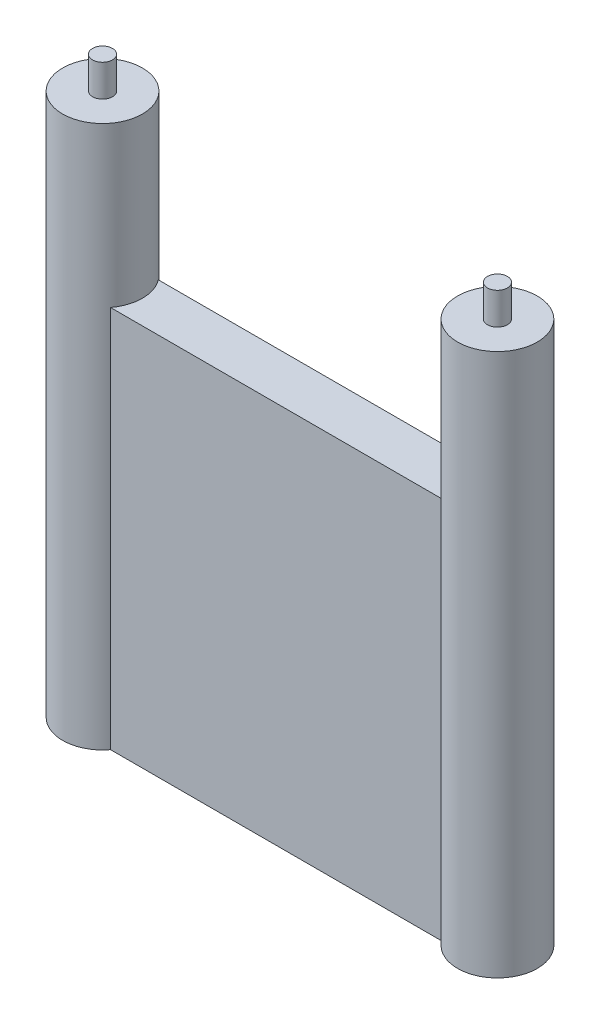
SolidWorks part; units mm, degrees
ref_plane "Front Plane" through (0, 0, 0) normal (0, 0, 1) x (1, 0, 0)
ref_plane "Top Plane" through (0, 0, 0) normal (0, 1, 0) x (1, 0, 0)
ref_plane "Right Plane" through (0, 0, 0) normal (1, 0, 0) x (0, 0, -1)
sketch "Sketch1" plane through (0, 0, 0) normal (0, 1, 0) x (1, 0, 0)
  line L0 (0, 0) -> (-49.5, 0)
  line L2 (-49.5, -3) -> (0, -3)
  line L3 (-49.5, -3) -> (-49.5, 3)
  line L4 (-49.5, 3) -> (0, 3)
  line L5 (0, -3) -> (0, 3)
  line L6 (-49.5, -3) -> (0, 3) construction
  line L7 (-49.5, 3) -> (0, -3) construction
  circle A0 centre (0, 0) radius 5
  circle A1 centre (-49.5, 0) radius 5
  point P5 (-24.75, 0)
  point P10 (0, 0)
  point P11 (0, 0)
  point P12 (0, 0)
  point P13 (0, 0)
  point P14 (0, 0)
  point P15 (0, 0)
  point P16 (0, 0)
  point P17 (0, 0)
  point P18 (0, 0)
  dimension "D1" = 10
  dimension "D2" = 10
  dimension "D3" = 49.5
  dimension "D4" = 6
  dimension "D5" = 0
extrude "Boss-Extrude2" add sketch "Sketch1" along normal blind 68 contours A1 | A0 | L3 L2 L5 L4
sketch "Sketch2" plane through (0, 68, 0) normal (0, 1, 0) x (1, 0, 0)
  line L0 (0, 0) -> (-49.5, 0) construction
  circle A0 centre (0, 0) radius 1.25
  circle A1 centre (-49.5, 0) radius 1.25
  dimension "D1" = 2.5
  dimension "D3" = 2.5
  dimension "D2" = 49.5
extrude "Boss-Extrude3" add sketch "Sketch2" along normal blind 4
sketch "Sketch3" plane through (0, 68, 0) normal (0, 1, 0) x (1, 0, 0)
  line L0 (-45.5, -3) -> (-4, -3) construction
  line L1 (-63.577, -23.2872) -> (14.077, -23.2872)
  line L2 (-63.577, -23.2872) -> (-63.577, 17.2872)
  line L3 (-63.577, 17.2872) -> (14.077, 17.2872)
  line L4 (14.077, -23.2872) -> (14.077, 17.2872)
  line L5 (-63.577, -23.2872) -> (14.077, 17.2872) construction
  line L6 (-63.577, 17.2872) -> (14.077, -23.2872) construction
  circle A0 centre (-49.5, 0) radius 5
  circle A1 centre (0, 0) radius 5
  point P6 (-24.75, -3)
  point P13 (-64.215, 17.2872)
  point P14 (-24.75, -3)
  dimension "D1" = 10
  dimension "D2" = 10
  dimension "D3" = 77.6541
  dimension "D4" = 40.5744
extrude "Cut-Extrude1" cut sketch "Sketch3" against normal blind 20
